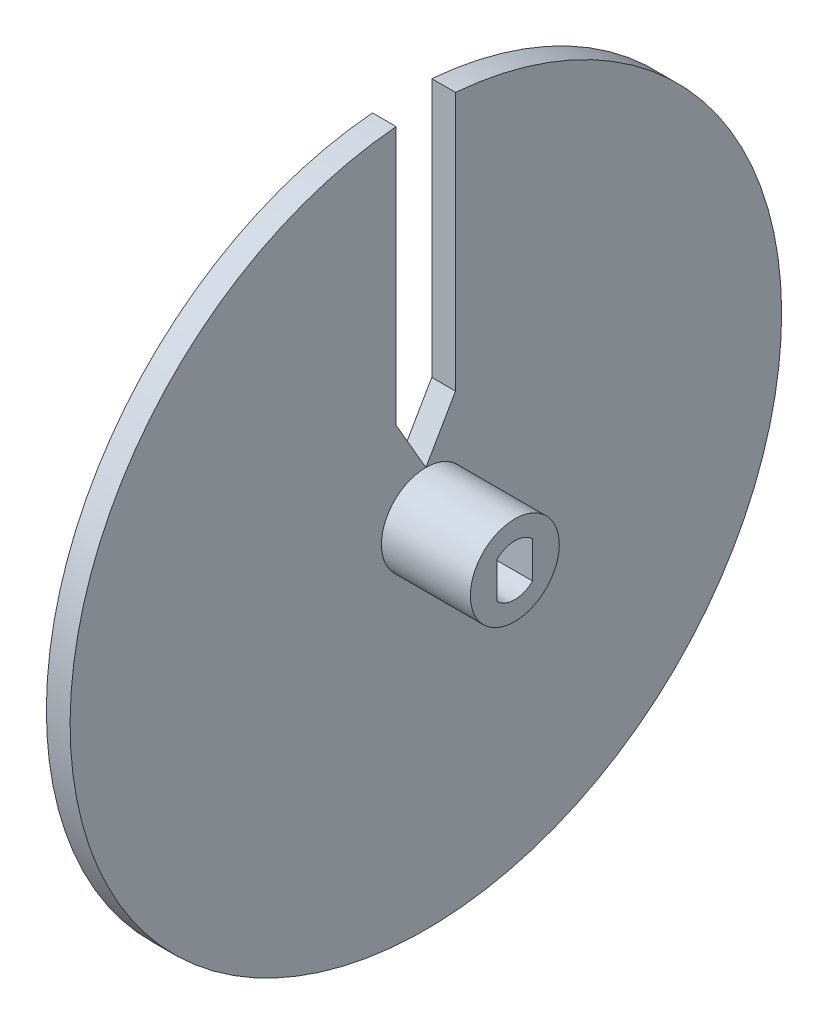
SolidWorks part; units mm, degrees
ref_plane "Front Plane" through (0, 0, 0) normal (0, 0, 1) x (1, 0, 0)
ref_plane "Top Plane" through (0, 0, 0) normal (0, 1, 0) x (1, 0, 0)
ref_plane "Right Plane" through (0, 0, 0) normal (1, 0, 0) x (0, 0, -1)
sketch "Sketch1" plane through (0, 0, 0) normal (1, 0, 0) x (0, 0, -1)
  line L0 (-1.905, -1.9562) -> (-1.905, 1.9562)
  line L1 (1.905, -1.9562) -> (1.905, 1.9562)
  arc A0 (-1.905, -1.9562) -> (1.905, -1.9562) centre (0, 0) ccw
  circle A1 centre (0, 0) radius 4.7625
  arc A2 (1.905, 1.9562) -> (-1.905, 1.9562) centre (0, 0) ccw
  dimension "D1" = 5.461
  dimension "D3" = 9.525
  dimension "D2" = 3.81
extrude "Boss-Extrude1" add sketch "Sketch1" along normal blind 9.525 contours A1
sketch "Sketch2" plane through (0, 0, 0) normal (-1, 0, 0) x (0, 0, 1)
  circle A0 centre (0, 0) radius 38.1
  dimension "D1" = 76.2
extrude "Boss-Extrude2" add sketch "Sketch2" along normal blind 2.54
sketch "Sketch3" plane through (0, 0, 0) normal (1, 0, 0) x (0, 0, -1)
  line L0 (-3.175, 10.2618) -> (0, 4.7625)
  line L1 (-3.175, 38.1) -> (3.175, 38.1)
  line L2 (-3.175, 38.1) -> (-3.175, 10.2618)
  line L4 (3.175, 38.1) -> (3.175, 10.2618)
  line L5 (0, 4.7625) -> (3.175, 10.2618)
  circle A0 centre (0, 0) radius 38.1 construction
  circle A2 centre (0, 0) radius 4.7625 construction
  circle A3 centre (0, 0) radius 4.7625 construction
  point P1 (0, 0)
  point P2 (0, 0)
  dimension "D1" = 6.35
  dimension "D2" = 30
extrude "Cut-Extrude1" cut sketch "Sketch3" against normal through all both and the other way through all contours L2 L0 L5 L4 L1
